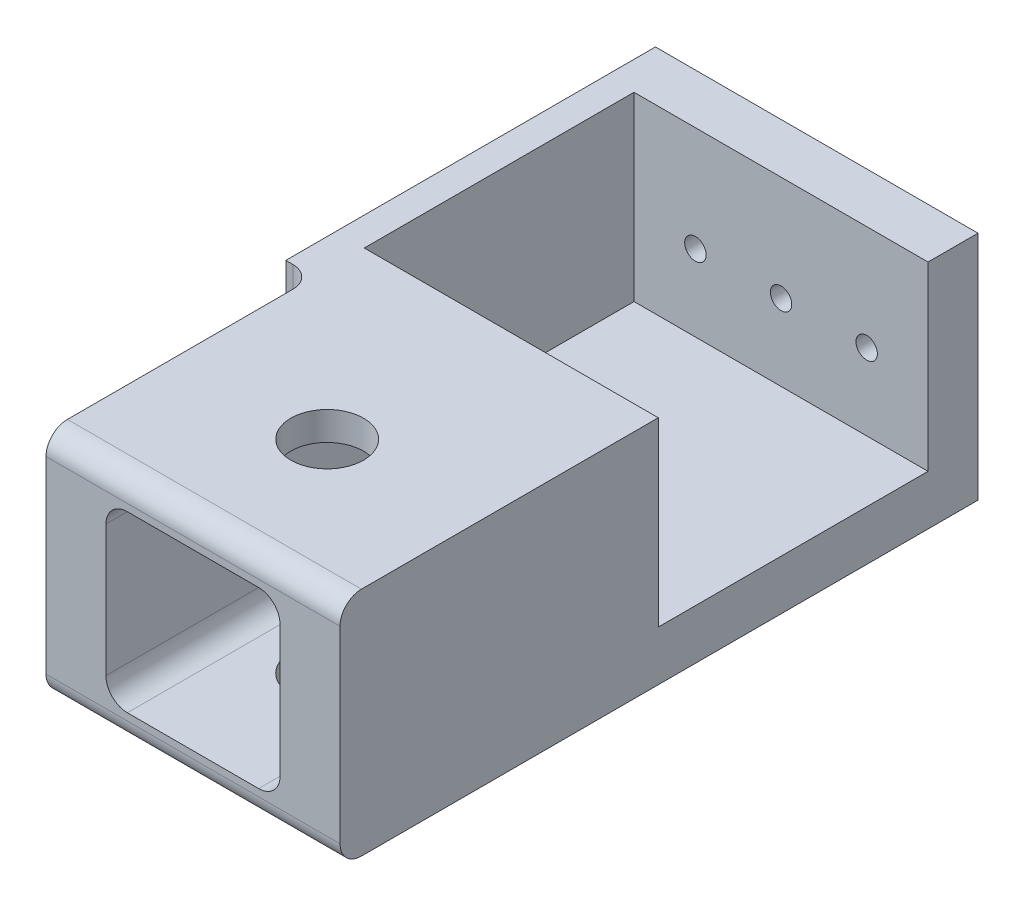
SolidWorks part; units mm, degrees
ref_plane "Спереди" through (0, 0, 0) normal (0, 0, 1) x (1, 0, 0)
ref_plane "Сверху" through (0, 0, 0) normal (0, 1, 0) x (1, 0, 0)
ref_plane "Справа" through (0, 0, 0) normal (1, 0, 0) x (0, 0, -1)
sketch "Эскиз1" plane through (0, 0, 0) normal (0, 1, 0) x (1, 0, 0)
  line L1 (-9.4, 9.45) -> (9.4, 9.45)
  line L3 (-9.4, -9.45) -> (9.4, -9.45)
  line L8 (9.4, -9.45) -> (-9.4, -9.45)
  line L9 (9.4, -9.45) -> (9.4, -12.95)
  line L10 (9.4, -12.95) -> (-9.4, -12.95)
  line L11 (-9.4, -9.45) -> (-9.4, -12.95)
  line L12 (9.4, 9.45) -> (-9.4, 9.45)
  line L13 (9.4, 9.45) -> (9.4, 12.95)
  line L14 (9.4, 12.95) -> (-9.4, 12.95)
  line L15 (-9.4, 9.45) -> (-9.4, 12.95)
  point P0 (0, 0)
  dimension "D1" = 18.8
  dimension "D2" = 18.9
  dimension "D3" = 3.5
  dimension "D4" = 3.5
extrude "Бобышка-Вытянуть1" add sketch "Эскиз1" along normal blind 12.7 contours L15 L1 L13 L14 | L3 L11 L10 L9
sketch "Эскиз2" plane through (0, 0, 0) normal (0, -1, 0) x (1, 0, 0)
  line L0 (9.4, -9.45) -> (9.4, -12.95) construction
  line L1 (-9.4, 12.95) -> (9.4, 12.95)
  line L2 (-9.4, 12.95) -> (-9.4, -12.95)
  line L3 (-9.4, -12.95) -> (9.4, -12.95)
  line L4 (9.4, 12.95) -> (9.4, -12.95)
  line L5 (9.4, -12.95) -> (-9.4, -12.95) construction
extrude "Бобышка-Вытянуть2" add sketch "Эскиз2" along normal blind 3.5
sketch "Эскиз3" plane through (-9.4, 0, 0) normal (-1, 0, 0) x (0, 0, 1)
  line L16 (-12.95, 12.7) -> (-12.95, -3.5)
  line L17 (-12.95, -3.5) -> (12.95, -3.5)
  line L18 (12.95, -3.5) -> (12.95, 12.7)
  line L19 (12.95, 12.7) -> (9.45, 12.7)
  line L20 (9.45, 12.7) -> (9.45, 0)
  line L21 (9.45, 0) -> (-9.45, 0)
  line L22 (-9.45, 0) -> (-9.45, 12.7)
  line L23 (-9.45, 12.7) -> (-12.95, 12.7)
  line L24 (-12.95, 12.7) -> (-12.95, -3.5)
  line L25 (-12.95, -3.5) -> (12.95, -3.5)
  line L26 (12.95, -3.5) -> (12.95, 12.7)
  line L27 (12.95, 12.7) -> (9.45, 12.7)
  line L28 (9.45, 12.7) -> (9.45, 0)
  line L29 (9.45, 0) -> (-9.45, 0)
  line L30 (-9.45, 0) -> (-9.45, 12.7)
  line L31 (-9.45, 12.7) -> (-12.95, 12.7)
  dimension "D1" = 0
extrude "Бобышка-Вытянуть3" add sketch "Эскиз3" along normal blind 1.8
sketch "Эскиз4" plane through (-11.2, 0, 0) normal (-1, 0, 0) x (0, 0, 1)
  line L1 (-12.95, 12.7) -> (12.95, 12.7)
  line L2 (-12.95, 12.7) -> (-12.95, -3.5)
  line L3 (-12.95, -3.5) -> (12.95, -3.5)
  line L4 (12.95, 12.7) -> (12.95, -3.5)
extrude "Бобышка-Вытянуть4" add sketch "Эскиз4" along normal blind 2
sketch "Эскиз5" plane through (0, 0, 12.95) normal (0, 0, 1) x (1, 0, 0)
  line L1 (-11.2, 12.7) -> (9.4, 12.7)
  line L2 (-11.2, 12.7) -> (-11.2, -3.5)
  line L3 (-11.2, -3.5) -> (9.4, -3.5)
  line L4 (9.4, 12.7) -> (9.4, -3.5)
extrude "Бобышка-Вытянуть5" add sketch "Эскиз5" along normal blind 18.8
sketch "Эскиз6" plane through (0, 0, 31.75) normal (0, 0, 1) x (1, 0, 0)
  line L0 (-11.2, 12.7) -> (9.4, -3.5) construction
  line L1 (-11.2, -3.5) -> (9.4, 12.7) construction
  line L3 (-7, 10.7) -> (5.2, 10.7)
  line L4 (-7, 10.7) -> (-7, -1.5)
  line L5 (-7, -1.5) -> (5.2, -1.5)
  line L6 (5.2, 10.7) -> (5.2, -1.5)
  line L7 (-7, 10.7) -> (5.2, -1.5) construction
  line L8 (-7, -1.5) -> (5.2, 10.7) construction
  point P8 (-0.9, 4.6)
  dimension "D1" = 12.2
  dimension "D2" = 12.2
extrude "Вырез-Вытянуть1" cut sketch "Эскиз6" against normal blind 18.8
fillet "Скругление1" radius 1.5 7 edges at (-0.9, -3.5, 31.75) (-0.9, 12.7, 31.75) (-11.2, 4.6, 12.95) (5.2, -1.5, 22.35) (-7, -1.5, 22.35) (5.2, 10.7, 22.35) (-7, 10.7, 22.35)
sketch "Эскиз7" plane through (0, -3.5, 0) normal (0, -1, 0) x (1, 0, 0)
  line L0 (-13.2, 22.35) -> (9.4, 22.35) construction
  line L5 (9.4, 12.95) -> (-11.2, 31.75) construction
  circle A0 centre (-0.9, 22.35) radius 2.55
  dimension "D1" = 5.1
extrude "Вырез-Вытянуть2" cut sketch "Эскиз7" against normal blind 18.8
sketch "Эскиз9" plane through (0, 0, -12.95) normal (0, 0, -1) x (-1, 0, 0)
  line L0 (11.2, -2) -> (-9.4, 12.7) construction
  line L1 (-9.4, -2) -> (11.2, 12.7) construction
  circle A0 centre (0.9, 5.35) radius 0.75
  circle A1 centre (6.9, 5.35) radius 0.75
  circle A2 centre (-5.1, 5.35) radius 0.75
  dimension "D1" = 1.5
  dimension "D2" = 2
  dimension "D3" = 2
extrude "Вырез-Вытянуть3" cut sketch "Эскиз9" against normal blind 7
